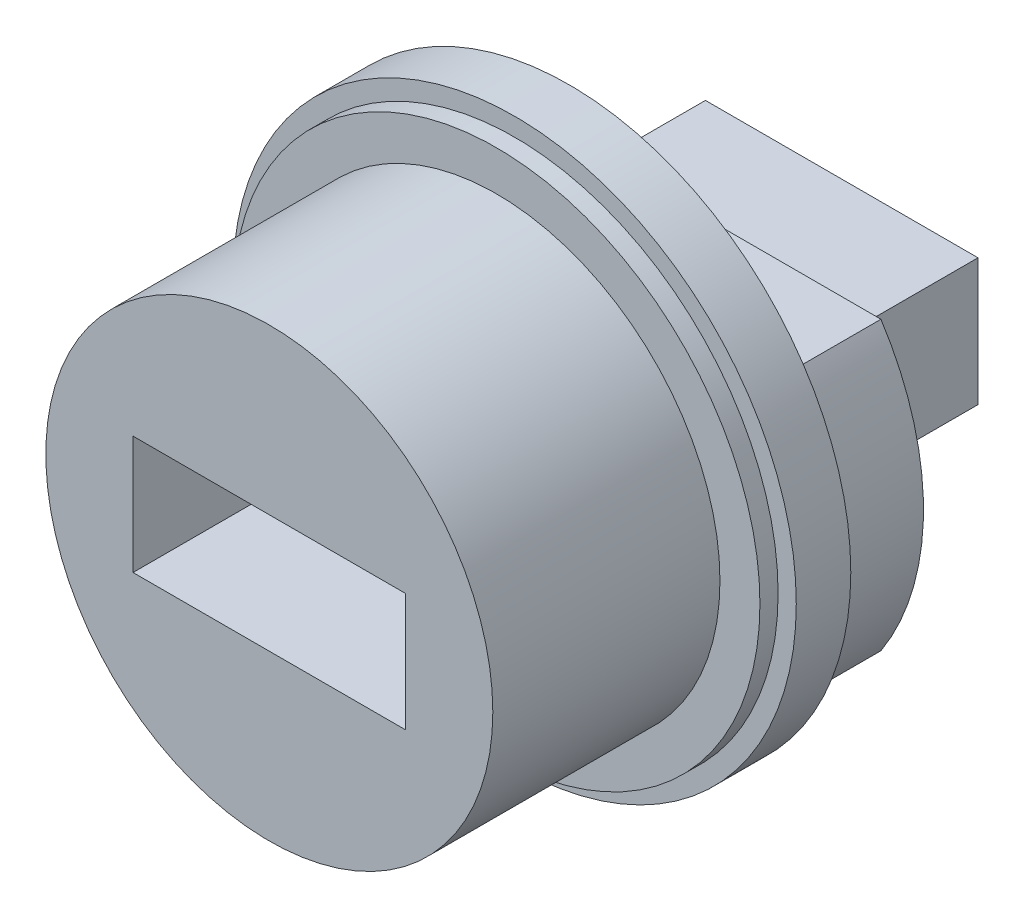
SolidWorks part; units mm, degrees
material "ABS"
ref_plane "正面" through (0, 0, 0) normal (0, 0, 1) x (1, 0, 0)
ref_plane "平面" through (0, 0, 0) normal (0, 1, 0) x (1, 0, 0)
ref_plane "右側面" through (0, 0, 0) normal (1, 0, 0) x (0, 0, -1)
sketch "ｽｹｯﾁ1" plane through (0, 0, 0) normal (0, 0, 1) x (1, 0, 0)
  circle A0 centre (0, 0) radius 15.5
  dimension "D1" = 31
extrude "ﾎﾞｽ - 押し出し1" add sketch "ｽｹｯﾁ1" along normal blind 3
sketch "ｽｹｯﾁ2" plane through (0, 0, 3) normal (0, 0, 1) x (1, 0, 0)
  circle A0 centre (0, 0) radius 14.5
  dimension "D1" = 29
extrude "ﾎﾞｽ - 押し出し2" add sketch "ｽｹｯﾁ2" along normal blind 1
sketch "ｽｹｯﾁ3" plane through (0, 0, 4) normal (0, 0, 1) x (1, 0, 0)
  circle A0 centre (0, 0) radius 12.3
  dimension "D1" = 24.6
extrude "ﾎﾞｽ - 押し出し3" add sketch "ｽｹｯﾁ3" along normal blind 12.5
sketch "ｽｹｯﾁ4" plane through (0, 0, 16.5) normal (0, 0, 1) x (1, 0, 0)
  line L1 (-7.5, -3.25) -> (7.5, -3.25)
  line L2 (-7.5, -3.25) -> (-7.5, 3.25)
  line L3 (-7.5, 3.25) -> (7.5, 3.25)
  line L4 (7.5, -3.25) -> (7.5, 3.25)
  line L5 (-7.5, -3.25) -> (7.5, 3.25) construction
  line L6 (-7.5, 3.25) -> (7.5, -3.25) construction
  point P0 (0, 0)
  dimension "D1" = 15
  dimension "D2" = 6.5
extrude "ｶｯﾄ - 押し出し1" cut sketch "ｽｹｯﾁ4" against normal blind 10
sketch "ｽｹｯﾁ5" plane through (0, 0, 0) normal (0, 0, -1) x (-1, 0, 0)
  line L1 (-12.1589, -7.9) -> (12.1589, -7.9)
  line L2 (-12.1589, -7.9) -> (-12.1589, 7.9) construction
  line L3 (-12.1589, 7.9) -> (12.1589, 7.9)
  line L5 (-12.1589, -7.9) -> (12.1589, 7.9) construction
  line L6 (-12.1589, 7.9) -> (12.1589, -7.9) construction
  arc A0 (-12.1589, 7.9) -> (-12.1589, -7.9) centre (0, 0) ccw
  arc A1 (12.1589, 7.9) -> (12.1589, -7.9) centre (0, 0) cw
  point P0 (0, 0)
  dimension "D1" = 15.8
  dimension "D2" = 29
extrude "ﾎﾞｽ - 押し出し4" add sketch "ｽｹｯﾁ5" along normal blind 5
sketch "ｽｹｯﾁ6" plane through (0, 0, -5) normal (0, 0, -1) x (-1, 0, 0)
  line L1 (-7.5, -3.5) -> (7.5, -3.5)
  line L2 (-7.5, -3.5) -> (-7.5, 3.5)
  line L3 (-7.5, 3.5) -> (7.5, 3.5)
  line L4 (7.5, -3.5) -> (7.5, 3.5)
  line L5 (-7.5, -3.5) -> (7.5, 3.5) construction
  line L6 (-7.5, 3.5) -> (7.5, -3.5) construction
  point P0 (0, 0)
  dimension "D1" = 15
  dimension "D2" = 7
extrude "ﾎﾞｽ - 押し出し5" add sketch "ｽｹｯﾁ6" along normal blind 10
